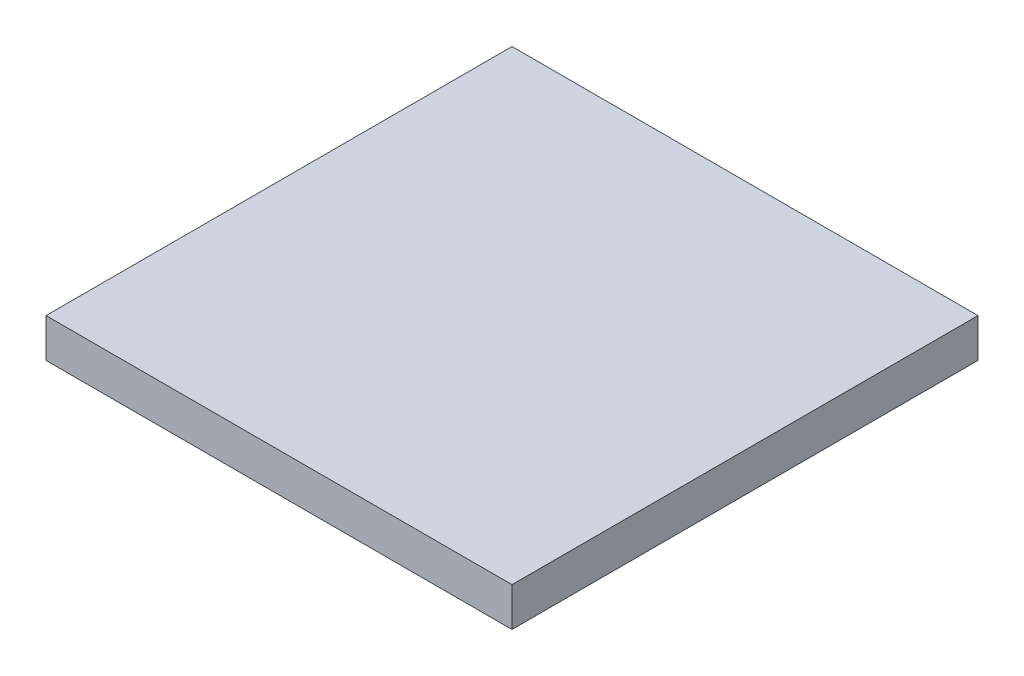
SolidWorks part; units mm, degrees
material "Pino"
ref_plane "Alzado" through (0, 0, 0) normal (0, 0, 1) x (1, 0, 0)
ref_plane "Planta" through (0, 0, 0) normal (0, 1, 0) x (1, 0, 0)
ref_plane "Vista lateral" through (0, 0, 0) normal (1, 0, 0) x (0, 0, -1)
sketch "Croquis1" plane through (0, 0, 0) normal (0, 1, 0) x (1, 0, 0)
  line L1 (-152.4, -152.4) -> (152.4, -152.4)
  line L2 (-152.4, -152.4) -> (-152.4, 152.4)
  line L3 (-152.4, 152.4) -> (152.4, 152.4)
  line L4 (152.4, -152.4) -> (152.4, 152.4)
  line L5 (-152.4, -152.4) -> (152.4, 152.4) construction
  line L6 (-152.4, 152.4) -> (152.4, -152.4) construction
  point P0 (0, 0)
  dimension "D1" = 304.8
  dimension "D2" = 304.8
extrude "Saliente-Extruir1" add sketch "Croquis1" along normal blind 25.4
